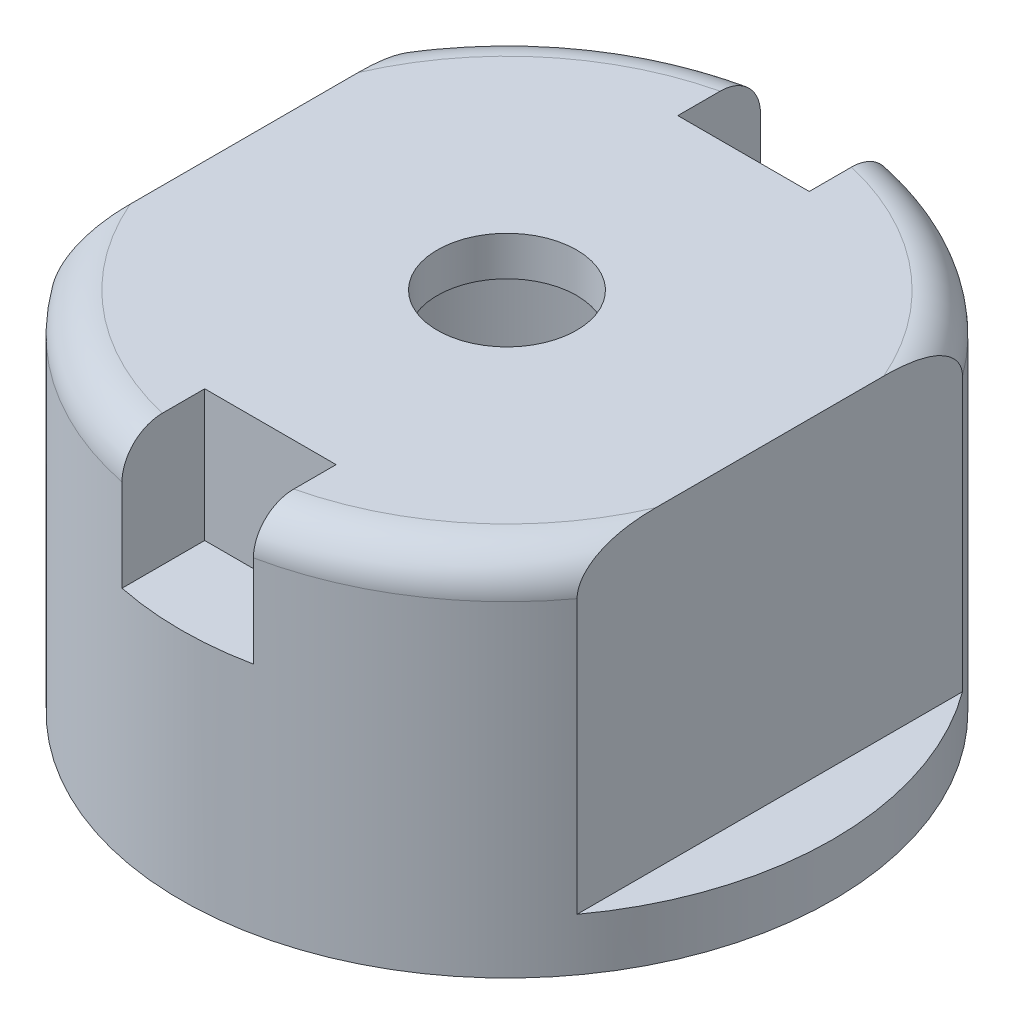
SolidWorks part; units mm, degrees
ref_plane "Plan de face" through (0, 0, 0) normal (0, 0, 1) x (1, 0, 0)
ref_plane "Plan de dessus" through (0, 0, 0) normal (0, 1, 0) x (1, 0, 0)
ref_plane "Plan de droite" through (0, 0, 0) normal (1, 0, 0) x (0, 0, -1)
sketch "Esquisse1" plane through (0, 0, 0) normal (0, 0, 1) x (1, 0, 0)
  line L0 (0, -3.6618) -> (0, 16.3977) construction
  line L1 (-8.4, 0) -> (-8.4, 11.4)
  line L2 (-7.4, 12.4) -> (-2.65, 12.4)
  line L3 (-2.65, 12.4) -> (-2.65, 13.9)
  line L6 (-2.65, 13.9) -> (-10.9, 13.9)
  line L7 (-12.4, 12.4) -> (-12.4, 0)
  line L8 (-12.4, 0) -> (-8.4, 0)
  arc A0 (-10.9, 13.9) -> (-12.4, 12.4) centre (-10.9, 12.4) ccw
  arc A1 (-8.4, 11.4) -> (-7.4, 12.4) centre (-7.4, 11.4) cw
  dimension "D1" = 24.8
  dimension "D4" = 1
  dimension "D8" = 1.5
  dimension "D2" = 4
  dimension "D3" = 13.9
  dimension "D5" = 1.5
  dimension "D6" = 5.3
revolve "Révolution1" add sketch "Esquisse1" angle 360 about L0
sketch "Esquisse2" plane through (0, 13.9, 0) normal (0, 1, 0) x (1, 0, 0)
  line L0 (0, 13.018) -> (0, -13.4783) construction
  line L1 (-10, 7.3321) -> (-10, -7.3321)
  line L2 (10, 7.3321) -> (10, -7.3321)
  arc A0 (-10, 7.3321) -> (-10, -7.3321) centre (0, 0) ccw
  circle A1 centre (0, 0) radius 12.4 construction
  arc A2 (10, 7.3321) -> (10, -7.3321) centre (0, 0) cw
  dimension "D1" = 20
extrude "Enlèv. mat.-Extru.1" cut sketch "Esquisse2" against normal offset from surface (11.9 mm away) 2 up to face at (0, 0, -8.4)
sketch "Esquisse3" plane through (0, 13.9, 0) normal (0, 1, 0) x (1, 0, 0)
  line L0 (-13.4927, 0) -> (13.4352, 0) construction
  line L1 (-2.5, 9) -> (2.5, 9)
  line L3 (2.5, -12.1454) -> (2.5, -9)
  line L4 (2.5, 12.1454) -> (2.5, 9)
  line L6 (-2.5, 12.1454) -> (-2.5, 9)
  line L7 (-2.5, -9) -> (2.5, -9)
  line L8 (-2.5, -12.1454) -> (-2.5, -9)
  arc A0 (-2.5, 12.1454) -> (2.5, 12.1454) centre (0, 0) cw
  arc A1 (10, 7.3321) -> (-10, 7.3321) centre (0, 0) ccw construction
  arc A2 (-2.5, -12.1454) -> (2.5, -12.1454) centre (0, 0) ccw
  point P4 (0, 9)
  dimension "D1" = 18
  dimension "D2" = 5
extrude "Enlèv. mat.-Extru.2" cut sketch "Esquisse3" against normal blind 5
hole_wizard "Trou pour taraudage pour trou taraudé M21" positions "Esquisse4" profile "Esquisse5" hole size "M2" standard "ISO"
sketch "Esquisse4" plane through (0, 0, 0) normal (0, -1, 0) x (-1, 0, 0)
  circle A10 centre (3.1019, 10.0345) radius 2 construction
  circle A11 centre (-9.0301, 5.3638) radius 2 construction
  circle A12 centre (9.0301, -5.3638) radius 2 construction
  circle A13 centre (-3.1019, -10.0345) radius 2 construction
  point P0 (-3.1019, -10.0345)
  point P3 (9.0301, -5.3638)
  point P6 (3.1019, 10.0345)
  point P9 (-9.0301, 5.3638)
sketch "Esquisse5" plane through (3.1019, 0, 10.0345) normal (1, 0, 0) x (0, 0, -1)
  line L0 (0, 0) -> (0, 8.4807)
  line L1 (0, 8.4807) -> (0.8, 8)
  line L2 (0.8, 8) -> (0.8, 0)
  line L5 (0.8, 0) -> (0, 0)
  line L10 (0, 8.4807) -> (-0.8, 8) construction
  line L11 (0, -6.35) -> (0, 107.95) construction
  dimension "Diamètre du perçage" = 1.6
  dimension "Profondeur du perçage" = 8
  dimension "Angle de pointe" = 118
